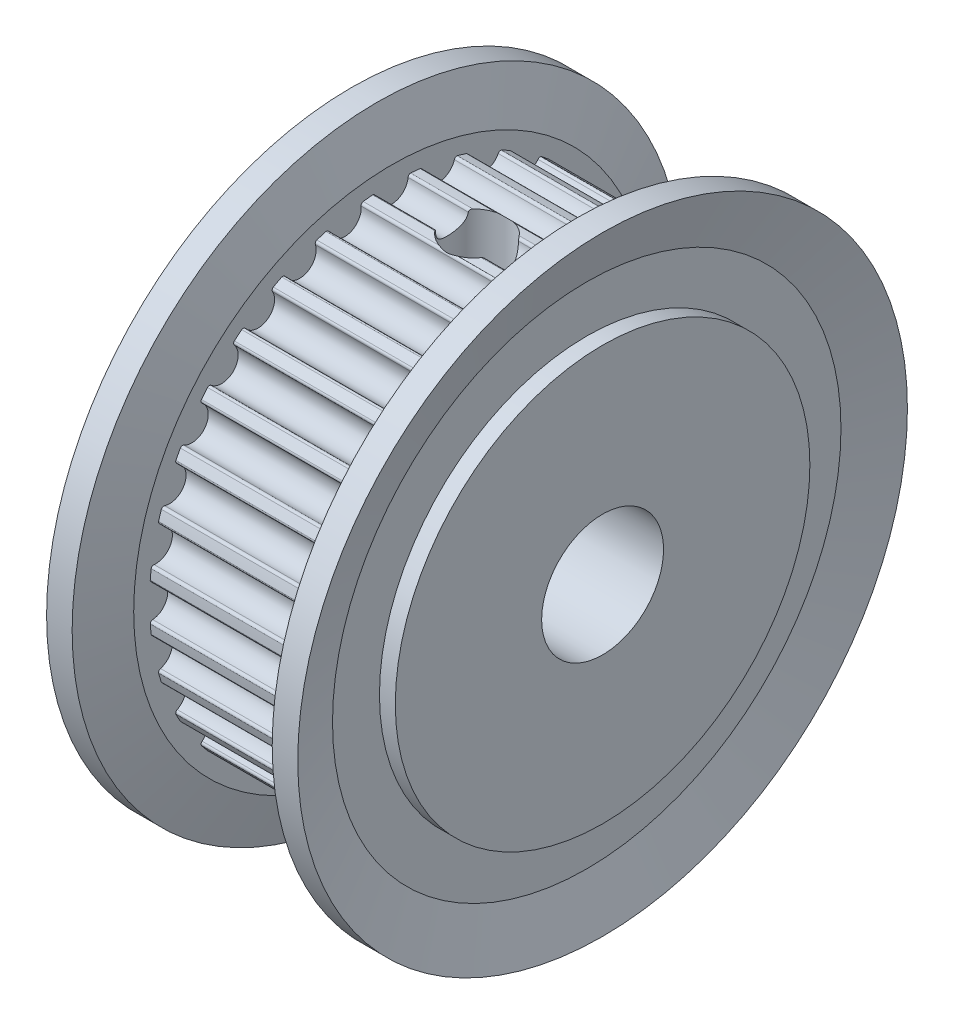
SolidWorks part; units mm, degrees
ref_plane "Front Plane" through (0, 0, 0) normal (0, 0, 1) x (1, 0, 0)
ref_plane "Top Plane" through (0, 0, 0) normal (0, 1, 0) x (1, 0, 0)
ref_plane "Right Plane" through (0, 0, 0) normal (1, 0, 0) x (0, 0, -1)
ref_plane "Plane1" through (0, 0, 0) normal (0, 0, 1) x (1, 0, 0)
sketch "Sketch1" plane through (0, 0, 0) normal (0, 0, 1) x (1, 0, 0)
  line L0 (-5.15, 0) -> (-5.15, 8.5)
  line L1 (-5.15, 8.5) -> (-3.5, 8.5)
  line L2 (-3.5, 8.5) -> (-3.5, 9.93)
  line L3 (-3.5, 9.93) -> (3.5, 9.93)
  line L4 (3.5, 9.93) -> (3.5, 8.5)
  line L5 (3.5, 8.5) -> (5.15, 8.5)
  line L6 (5.15, 8.5) -> (5.15, 0)
  line L7 (5.15, 0) -> (-5.15, 0)
  line L8 (5.15, 0) -> (-5.15, 0) construction
revolve "Revolve1" add sketch "Sketch1" angle 360 about L8
ref_plane "Plane2" through (0, 0, 0) normal (1, 0, 0) x (0, 0, -1)
sketch "Sketch2" plane through (0, 0, 0) normal (1, 0, 0) x (0, 0, -1)
  line L0 (-0.9509, 10.1405) -> (-0.9273, 9.8885)
  line L1 (-0.9273, 9.8885) -> (-0.793, 9.8993)
  line L2 (0.793, 9.8993) -> (0.9273, 9.8885)
  line L3 (0.9273, 9.8885) -> (0.9509, 10.1405)
  arc A0 (-0.793, 9.8993) -> (-0.6724, 9.7974) centre (-0.784, 9.7876) cw
  arc A1 (-0.6724, 9.7974) -> (0.6724, 9.7974) centre (0, 9.856) ccw
  arc A2 (0.6724, 9.7974) -> (0.793, 9.8993) centre (0.784, 9.7876) cw
  arc A3 (0.9509, 10.1405) -> (-0.9509, 10.1405) centre (0, 0) ccw
extrude "Cut-Extrude1" cut sketch "Sketch2" against normal blind 3.5 and the other way blind 3.5
ref_plane "Plane3" through (0, 0, 0) normal (1, 0, 0) x (0, 0, -1)
sketch "Sketch3" plane through (0, 0, 0) normal (1, 0, 0) x (0, 0, -1)
  line L0 (-2.911, 9.7602) -> (-2.8386, 9.5176)
  line L1 (-2.8386, 9.5176) -> (-2.709, 9.5544)
  line L2 (-1.1535, 9.8638) -> (-1.0197, 9.8794)
  line L3 (-1.0197, 9.8794) -> (-1.0457, 10.1312)
  arc A0 (-2.709, 9.5544) -> (-2.5709, 9.4779) centre (-2.6784, 9.4466) cw
  arc A1 (-2.5709, 9.4779) -> (-1.2518, 9.7403) centre (-1.9228, 9.6666) ccw
  arc A2 (-1.2518, 9.7403) -> (-1.1535, 9.8638) centre (-1.1405, 9.7525) cw
  arc A3 (-1.0457, 10.1312) -> (-2.911, 9.7602) centre (0, 0) ccw
extrude "Cut-Extrude2" cut sketch "Sketch3" against normal blind 3.5 and the other way blind 3.5
ref_plane "Plane4" through (0, 0, 0) normal (1, 0, 0) x (0, 0, -1)
sketch "Sketch4" plane through (0, 0, 0) normal (1, 0, 0) x (0, 0, -1)
  line L0 (-4.7591, 9.0047) -> (-4.6409, 8.781)
  line L1 (-4.6409, 8.781) -> (-4.5209, 8.8423)
  line L2 (-3.0557, 9.4492) -> (-2.9275, 9.4907)
  line L3 (-2.9275, 9.4907) -> (-3.0021, 9.7325)
  arc A0 (-4.5209, 8.8423) -> (-4.3706, 8.7943) centre (-4.4699, 8.7426) cw
  arc A1 (-4.3706, 8.7943) -> (-3.128, 9.3089) centre (-3.7717, 9.1058) ccw
  arc A2 (-3.128, 9.3089) -> (-3.0557, 9.4492) centre (-3.0212, 9.3426) cw
  arc A3 (-3.0021, 9.7325) -> (-4.7591, 9.0047) centre (0, 0) ccw
extrude "Cut-Extrude3" cut sketch "Sketch4" against normal blind 3.5 and the other way blind 3.5
ref_plane "Plane5" through (0, 0, 0) normal (1, 0, 0) x (0, 0, -1)
sketch "Sketch5" plane through (0, 0, 0) normal (1, 0, 0) x (0, 0, -1)
  line L0 (-6.4244, 7.9032) -> (-6.2648, 7.7068)
  line L1 (-6.2648, 7.7068) -> (-6.1591, 7.7904)
  line L2 (-4.8404, 8.6715) -> (-4.7228, 8.7372)
  line L3 (-4.7228, 8.7372) -> (-4.8431, 8.9598)
  arc A0 (-6.1591, 7.7904) -> (-6.0023, 7.7726) centre (-6.0896, 7.7026) cw
  arc A1 (-6.0023, 7.7726) -> (-4.884, 8.5198) centre (-5.4757, 8.195) ccw
  arc A2 (-4.884, 8.5198) -> (-4.8404, 8.6715) centre (-4.7858, 8.5737) cw
  arc A3 (-4.8431, 8.9598) -> (-6.4244, 7.9032) centre (0, 0) ccw
extrude "Cut-Extrude4" cut sketch "Sketch5" against normal blind 3.5 and the other way blind 3.5
ref_plane "Plane6" through (0, 0, 0) normal (1, 0, 0) x (0, 0, -1)
sketch "Sketch6" plane through (0, 0, 0) normal (1, 0, 0) x (0, 0, -1)
  line L0 (-7.8428, 6.498) -> (-7.6479, 6.3366)
  line L1 (-7.6479, 6.3366) -> (-7.5606, 6.4391)
  line L2 (-6.4391, 7.5606) -> (-6.3366, 7.6479)
  line L3 (-6.3366, 7.6479) -> (-6.498, 7.8428)
  arc A0 (-7.5606, 6.4391) -> (-7.4033, 6.4523) centre (-7.4753, 6.3665) cw
  arc A1 (-7.4033, 6.4523) -> (-6.4523, 7.4033) centre (-6.9692, 6.9692) ccw
  arc A2 (-6.4523, 7.4033) -> (-6.4391, 7.5606) centre (-6.3665, 7.4753) cw
  arc A3 (-6.498, 7.8428) -> (-7.8428, 6.498) centre (0, 0) ccw
extrude "Cut-Extrude5" cut sketch "Sketch6" against normal blind 3.5 and the other way blind 3.5
ref_plane "Plane7" through (0, 0, 0) normal (1, 0, 0) x (0, 0, -1)
sketch "Sketch7" plane through (0, 0, 0) normal (1, 0, 0) x (0, 0, -1)
  line L0 (-8.9598, 4.8431) -> (-8.7372, 4.7228)
  line L1 (-8.7372, 4.7228) -> (-8.6715, 4.8404)
  line L2 (-7.7904, 6.1591) -> (-7.7068, 6.2648)
  line L3 (-7.7068, 6.2648) -> (-7.9032, 6.4244)
  arc A0 (-8.6715, 4.8404) -> (-8.5198, 4.884) centre (-8.5737, 4.7858) cw
  arc A1 (-8.5198, 4.884) -> (-7.7726, 6.0023) centre (-8.195, 5.4757) ccw
  arc A2 (-7.7726, 6.0023) -> (-7.7904, 6.1591) centre (-7.7026, 6.0896) cw
  arc A3 (-7.9032, 6.4244) -> (-8.9598, 4.8431) centre (0, 0) ccw
extrude "Cut-Extrude6" cut sketch "Sketch7" against normal blind 3.5 and the other way blind 3.5
ref_plane "Plane8" through (0, 0, 0) normal (1, 0, 0) x (0, 0, -1)
sketch "Sketch8" plane through (0, 0, 0) normal (1, 0, 0) x (0, 0, -1)
  line L0 (-9.7325, 3.0021) -> (-9.4907, 2.9275)
  line L1 (-9.4907, 2.9275) -> (-9.4492, 3.0557)
  line L2 (-8.8423, 4.5209) -> (-8.781, 4.6409)
  line L3 (-8.781, 4.6409) -> (-9.0047, 4.7591)
  arc A0 (-9.4492, 3.0557) -> (-9.3089, 3.128) centre (-9.3426, 3.0212) cw
  arc A1 (-9.3089, 3.128) -> (-8.7943, 4.3706) centre (-9.1058, 3.7717) ccw
  arc A2 (-8.7943, 4.3706) -> (-8.8423, 4.5209) centre (-8.7426, 4.4699) cw
  arc A3 (-9.0047, 4.7591) -> (-9.7325, 3.0021) centre (0, 0) ccw
extrude "Cut-Extrude7" cut sketch "Sketch8" against normal blind 3.5 and the other way blind 3.5
ref_plane "Plane9" through (0, 0, 0) normal (1, 0, 0) x (0, 0, -1)
sketch "Sketch9" plane through (0, 0, 0) normal (1, 0, 0) x (0, 0, -1)
  line L0 (-10.1312, 1.0457) -> (-9.8794, 1.0197)
  line L1 (-9.8794, 1.0197) -> (-9.8638, 1.1535)
  line L2 (-9.5544, 2.709) -> (-9.5176, 2.8386)
  line L3 (-9.5176, 2.8386) -> (-9.7602, 2.911)
  arc A0 (-9.8638, 1.1535) -> (-9.7403, 1.2518) centre (-9.7525, 1.1405) cw
  arc A1 (-9.7403, 1.2518) -> (-9.4779, 2.5709) centre (-9.6666, 1.9228) ccw
  arc A2 (-9.4779, 2.5709) -> (-9.5544, 2.709) centre (-9.4466, 2.6784) cw
  arc A3 (-9.7602, 2.911) -> (-10.1312, 1.0457) centre (0, 0) ccw
extrude "Cut-Extrude8" cut sketch "Sketch9" against normal blind 3.5 and the other way blind 3.5
ref_plane "Plane10" through (0, 0, 0) normal (1, 0, 0) x (0, 0, -1)
sketch "Sketch10" plane through (0, 0, 0) normal (1, 0, 0) x (0, 0, -1)
  line L0 (-10.1405, -0.9509) -> (-9.8885, -0.9273)
  line L1 (-9.8885, -0.9273) -> (-9.8993, -0.793)
  line L2 (-9.8993, 0.793) -> (-9.8885, 0.9273)
  line L3 (-9.8885, 0.9273) -> (-10.1405, 0.9509)
  arc A0 (-9.8993, -0.793) -> (-9.7974, -0.6724) centre (-9.7876, -0.784) cw
  arc A1 (-9.7974, -0.6724) -> (-9.7974, 0.6724) centre (-9.856, 0) ccw
  arc A2 (-9.7974, 0.6724) -> (-9.8993, 0.793) centre (-9.7876, 0.784) cw
  arc A3 (-10.1405, 0.9509) -> (-10.1405, -0.9509) centre (0, 0) ccw
extrude "Cut-Extrude9" cut sketch "Sketch10" against normal blind 3.5 and the other way blind 3.5
ref_plane "Plane11" through (0, 0, 0) normal (1, 0, 0) x (0, 0, -1)
sketch "Sketch11" plane through (0, 0, 0) normal (1, 0, 0) x (0, 0, -1)
  line L0 (-9.7602, -2.911) -> (-9.5176, -2.8386)
  line L1 (-9.5176, -2.8386) -> (-9.5544, -2.709)
  line L2 (-9.8638, -1.1535) -> (-9.8794, -1.0197)
  line L3 (-9.8794, -1.0197) -> (-10.1312, -1.0457)
  arc A0 (-9.5544, -2.709) -> (-9.4779, -2.5709) centre (-9.4466, -2.6784) cw
  arc A1 (-9.4779, -2.5709) -> (-9.7403, -1.2518) centre (-9.6666, -1.9228) ccw
  arc A2 (-9.7403, -1.2518) -> (-9.8638, -1.1535) centre (-9.7525, -1.1405) cw
  arc A3 (-10.1312, -1.0457) -> (-9.7602, -2.911) centre (0, 0) ccw
extrude "Cut-Extrude10" cut sketch "Sketch11" against normal blind 3.5 and the other way blind 3.5
ref_plane "Plane12" through (0, 0, 0) normal (1, 0, 0) x (0, 0, -1)
sketch "Sketch12" plane through (0, 0, 0) normal (1, 0, 0) x (0, 0, -1)
  line L0 (-9.0047, -4.7591) -> (-8.781, -4.6409)
  line L1 (-8.781, -4.6409) -> (-8.8423, -4.5209)
  line L2 (-9.4492, -3.0557) -> (-9.4907, -2.9275)
  line L3 (-9.4907, -2.9275) -> (-9.7325, -3.0021)
  arc A0 (-8.8423, -4.5209) -> (-8.7943, -4.3706) centre (-8.7426, -4.4699) cw
  arc A1 (-8.7943, -4.3706) -> (-9.3089, -3.128) centre (-9.1058, -3.7717) ccw
  arc A2 (-9.3089, -3.128) -> (-9.4492, -3.0557) centre (-9.3426, -3.0212) cw
  arc A3 (-9.7325, -3.0021) -> (-9.0047, -4.7591) centre (0, 0) ccw
extrude "Cut-Extrude11" cut sketch "Sketch12" against normal blind 3.5 and the other way blind 3.5
ref_plane "Plane13" through (0, 0, 0) normal (1, 0, 0) x (0, 0, -1)
sketch "Sketch13" plane through (0, 0, 0) normal (1, 0, 0) x (0, 0, -1)
  line L0 (-7.9032, -6.4244) -> (-7.7068, -6.2648)
  line L1 (-7.7068, -6.2648) -> (-7.7904, -6.1591)
  line L2 (-8.6715, -4.8404) -> (-8.7372, -4.7228)
  line L3 (-8.7372, -4.7228) -> (-8.9598, -4.8431)
  arc A0 (-7.7904, -6.1591) -> (-7.7726, -6.0023) centre (-7.7026, -6.0896) cw
  arc A1 (-7.7726, -6.0023) -> (-8.5198, -4.884) centre (-8.195, -5.4757) ccw
  arc A2 (-8.5198, -4.884) -> (-8.6715, -4.8404) centre (-8.5737, -4.7858) cw
  arc A3 (-8.9598, -4.8431) -> (-7.9032, -6.4244) centre (0, 0) ccw
extrude "Cut-Extrude12" cut sketch "Sketch13" against normal blind 3.5 and the other way blind 3.5
ref_plane "Plane14" through (0, 0, 0) normal (1, 0, 0) x (0, 0, -1)
sketch "Sketch14" plane through (0, 0, 0) normal (1, 0, 0) x (0, 0, -1)
  line L0 (-6.498, -7.8428) -> (-6.3366, -7.6479)
  line L1 (-6.3366, -7.6479) -> (-6.4391, -7.5606)
  line L2 (-7.5606, -6.4391) -> (-7.6479, -6.3366)
  line L3 (-7.6479, -6.3366) -> (-7.8428, -6.498)
  arc A0 (-6.4391, -7.5606) -> (-6.4523, -7.4033) centre (-6.3665, -7.4753) cw
  arc A1 (-6.4523, -7.4033) -> (-7.4033, -6.4523) centre (-6.9692, -6.9692) ccw
  arc A2 (-7.4033, -6.4523) -> (-7.5606, -6.4391) centre (-7.4753, -6.3665) cw
  arc A3 (-7.8428, -6.498) -> (-6.498, -7.8428) centre (0, 0) ccw
extrude "Cut-Extrude13" cut sketch "Sketch14" against normal blind 3.5 and the other way blind 3.5
ref_plane "Plane15" through (0, 0, 0) normal (1, 0, 0) x (0, 0, -1)
sketch "Sketch15" plane through (0, 0, 0) normal (1, 0, 0) x (0, 0, -1)
  line L0 (-4.8431, -8.9598) -> (-4.7228, -8.7372)
  line L1 (-4.7228, -8.7372) -> (-4.8404, -8.6715)
  line L2 (-6.1591, -7.7904) -> (-6.2648, -7.7068)
  line L3 (-6.2648, -7.7068) -> (-6.4244, -7.9032)
  arc A0 (-4.8404, -8.6715) -> (-4.884, -8.5198) centre (-4.7858, -8.5737) cw
  arc A1 (-4.884, -8.5198) -> (-6.0023, -7.7726) centre (-5.4757, -8.195) ccw
  arc A2 (-6.0023, -7.7726) -> (-6.1591, -7.7904) centre (-6.0896, -7.7026) cw
  arc A3 (-6.4244, -7.9032) -> (-4.8431, -8.9598) centre (0, 0) ccw
extrude "Cut-Extrude14" cut sketch "Sketch15" against normal blind 3.5 and the other way blind 3.5
ref_plane "Plane16" through (0, 0, 0) normal (1, 0, 0) x (0, 0, -1)
sketch "Sketch16" plane through (0, 0, 0) normal (1, 0, 0) x (0, 0, -1)
  line L0 (-3.0021, -9.7325) -> (-2.9275, -9.4907)
  line L1 (-2.9275, -9.4907) -> (-3.0557, -9.4492)
  line L2 (-4.5209, -8.8423) -> (-4.6409, -8.781)
  line L3 (-4.6409, -8.781) -> (-4.7591, -9.0047)
  arc A0 (-3.0557, -9.4492) -> (-3.128, -9.3089) centre (-3.0212, -9.3426) cw
  arc A1 (-3.128, -9.3089) -> (-4.3706, -8.7943) centre (-3.7717, -9.1058) ccw
  arc A2 (-4.3706, -8.7943) -> (-4.5209, -8.8423) centre (-4.4699, -8.7426) cw
  arc A3 (-4.7591, -9.0047) -> (-3.0021, -9.7325) centre (0, 0) ccw
extrude "Cut-Extrude15" cut sketch "Sketch16" against normal blind 3.5 and the other way blind 3.5
ref_plane "Plane17" through (0, 0, 0) normal (1, 0, 0) x (0, 0, -1)
sketch "Sketch17" plane through (0, 0, 0) normal (1, 0, 0) x (0, 0, -1)
  line L0 (-1.0457, -10.1312) -> (-1.0197, -9.8794)
  line L1 (-1.0197, -9.8794) -> (-1.1535, -9.8638)
  line L2 (-2.709, -9.5544) -> (-2.8386, -9.5176)
  line L3 (-2.8386, -9.5176) -> (-2.911, -9.7602)
  arc A0 (-1.1535, -9.8638) -> (-1.2518, -9.7403) centre (-1.1405, -9.7525) cw
  arc A1 (-1.2518, -9.7403) -> (-2.5709, -9.4779) centre (-1.9228, -9.6666) ccw
  arc A2 (-2.5709, -9.4779) -> (-2.709, -9.5544) centre (-2.6784, -9.4466) cw
  arc A3 (-2.911, -9.7602) -> (-1.0457, -10.1312) centre (0, 0) ccw
extrude "Cut-Extrude16" cut sketch "Sketch17" against normal blind 3.5 and the other way blind 3.5
ref_plane "Plane18" through (0, 0, 0) normal (1, 0, 0) x (0, 0, -1)
sketch "Sketch18" plane through (0, 0, 0) normal (1, 0, 0) x (0, 0, -1)
  line L0 (0.9509, -10.1405) -> (0.9273, -9.8885)
  line L1 (0.9273, -9.8885) -> (0.793, -9.8993)
  line L2 (-0.793, -9.8993) -> (-0.9273, -9.8885)
  line L3 (-0.9273, -9.8885) -> (-0.9509, -10.1405)
  arc A0 (0.793, -9.8993) -> (0.6724, -9.7974) centre (0.784, -9.7876) cw
  arc A1 (0.6724, -9.7974) -> (-0.6724, -9.7974) centre (0, -9.856) ccw
  arc A2 (-0.6724, -9.7974) -> (-0.793, -9.8993) centre (-0.784, -9.7876) cw
  arc A3 (-0.9509, -10.1405) -> (0.9509, -10.1405) centre (0, 0) ccw
extrude "Cut-Extrude17" cut sketch "Sketch18" against normal blind 3.5 and the other way blind 3.5
ref_plane "Plane19" through (0, 0, 0) normal (1, 0, 0) x (0, 0, -1)
sketch "Sketch19" plane through (0, 0, 0) normal (1, 0, 0) x (0, 0, -1)
  line L0 (2.911, -9.7602) -> (2.8386, -9.5176)
  line L1 (2.8386, -9.5176) -> (2.709, -9.5544)
  line L2 (1.1535, -9.8638) -> (1.0197, -9.8794)
  line L3 (1.0197, -9.8794) -> (1.0457, -10.1312)
  arc A0 (2.709, -9.5544) -> (2.5709, -9.4779) centre (2.6784, -9.4466) cw
  arc A1 (2.5709, -9.4779) -> (1.2518, -9.7403) centre (1.9228, -9.6666) ccw
  arc A2 (1.2518, -9.7403) -> (1.1535, -9.8638) centre (1.1405, -9.7525) cw
  arc A3 (1.0457, -10.1312) -> (2.911, -9.7602) centre (0, 0) ccw
extrude "Cut-Extrude18" cut sketch "Sketch19" against normal blind 3.5 and the other way blind 3.5
ref_plane "Plane20" through (0, 0, 0) normal (1, 0, 0) x (0, 0, -1)
sketch "Sketch20" plane through (0, 0, 0) normal (1, 0, 0) x (0, 0, -1)
  line L0 (4.7591, -9.0047) -> (4.6409, -8.781)
  line L1 (4.6409, -8.781) -> (4.5209, -8.8423)
  line L2 (3.0557, -9.4492) -> (2.9275, -9.4907)
  line L3 (2.9275, -9.4907) -> (3.0021, -9.7325)
  arc A0 (4.5209, -8.8423) -> (4.3706, -8.7943) centre (4.4699, -8.7426) cw
  arc A1 (4.3706, -8.7943) -> (3.128, -9.3089) centre (3.7717, -9.1058) ccw
  arc A2 (3.128, -9.3089) -> (3.0557, -9.4492) centre (3.0212, -9.3426) cw
  arc A3 (3.0021, -9.7325) -> (4.7591, -9.0047) centre (0, 0) ccw
extrude "Cut-Extrude19" cut sketch "Sketch20" against normal blind 3.5 and the other way blind 3.5
ref_plane "Plane21" through (0, 0, 0) normal (1, 0, 0) x (0, 0, -1)
sketch "Sketch21" plane through (0, 0, 0) normal (1, 0, 0) x (0, 0, -1)
  line L0 (6.4244, -7.9032) -> (6.2648, -7.7068)
  line L1 (6.2648, -7.7068) -> (6.1591, -7.7904)
  line L2 (4.8404, -8.6715) -> (4.7228, -8.7372)
  line L3 (4.7228, -8.7372) -> (4.8431, -8.9598)
  arc A0 (6.1591, -7.7904) -> (6.0023, -7.7726) centre (6.0896, -7.7026) cw
  arc A1 (6.0023, -7.7726) -> (4.884, -8.5198) centre (5.4757, -8.195) ccw
  arc A2 (4.884, -8.5198) -> (4.8404, -8.6715) centre (4.7858, -8.5737) cw
  arc A3 (4.8431, -8.9598) -> (6.4244, -7.9032) centre (0, 0) ccw
extrude "Cut-Extrude20" cut sketch "Sketch21" against normal blind 3.5 and the other way blind 3.5
ref_plane "Plane22" through (0, 0, 0) normal (1, 0, 0) x (0, 0, -1)
sketch "Sketch22" plane through (0, 0, 0) normal (1, 0, 0) x (0, 0, -1)
  line L0 (7.8428, -6.498) -> (7.6479, -6.3366)
  line L1 (7.6479, -6.3366) -> (7.5606, -6.4391)
  line L2 (6.4391, -7.5606) -> (6.3366, -7.6479)
  line L3 (6.3366, -7.6479) -> (6.498, -7.8428)
  arc A0 (7.5606, -6.4391) -> (7.4033, -6.4523) centre (7.4753, -6.3665) cw
  arc A1 (7.4033, -6.4523) -> (6.4523, -7.4033) centre (6.9692, -6.9692) ccw
  arc A2 (6.4523, -7.4033) -> (6.4391, -7.5606) centre (6.3665, -7.4753) cw
  arc A3 (6.498, -7.8428) -> (7.8428, -6.498) centre (0, 0) ccw
extrude "Cut-Extrude21" cut sketch "Sketch22" against normal blind 3.5 and the other way blind 3.5
ref_plane "Plane23" through (0, 0, 0) normal (1, 0, 0) x (0, 0, -1)
sketch "Sketch23" plane through (0, 0, 0) normal (1, 0, 0) x (0, 0, -1)
  line L0 (8.9598, -4.8431) -> (8.7372, -4.7228)
  line L1 (8.7372, -4.7228) -> (8.6715, -4.8404)
  line L2 (7.7904, -6.1591) -> (7.7068, -6.2648)
  line L3 (7.7068, -6.2648) -> (7.9032, -6.4244)
  arc A0 (8.6715, -4.8404) -> (8.5198, -4.884) centre (8.5737, -4.7858) cw
  arc A1 (8.5198, -4.884) -> (7.7726, -6.0023) centre (8.195, -5.4757) ccw
  arc A2 (7.7726, -6.0023) -> (7.7904, -6.1591) centre (7.7026, -6.0896) cw
  arc A3 (7.9032, -6.4244) -> (8.9598, -4.8431) centre (0, 0) ccw
extrude "Cut-Extrude22" cut sketch "Sketch23" against normal blind 3.5 and the other way blind 3.5
ref_plane "Plane24" through (0, 0, 0) normal (1, 0, 0) x (0, 0, -1)
sketch "Sketch24" plane through (0, 0, 0) normal (1, 0, 0) x (0, 0, -1)
  line L0 (9.7325, -3.0021) -> (9.4907, -2.9275)
  line L1 (9.4907, -2.9275) -> (9.4492, -3.0557)
  line L2 (8.8423, -4.5209) -> (8.781, -4.6409)
  line L3 (8.781, -4.6409) -> (9.0047, -4.7591)
  arc A0 (9.4492, -3.0557) -> (9.3089, -3.128) centre (9.3426, -3.0212) cw
  arc A1 (9.3089, -3.128) -> (8.7943, -4.3706) centre (9.1058, -3.7717) ccw
  arc A2 (8.7943, -4.3706) -> (8.8423, -4.5209) centre (8.7426, -4.4699) cw
  arc A3 (9.0047, -4.7591) -> (9.7325, -3.0021) centre (0, 0) ccw
extrude "Cut-Extrude23" cut sketch "Sketch24" against normal blind 3.5 and the other way blind 3.5
ref_plane "Plane25" through (0, 0, 0) normal (1, 0, 0) x (0, 0, -1)
sketch "Sketch25" plane through (0, 0, 0) normal (1, 0, 0) x (0, 0, -1)
  line L0 (10.1312, -1.0457) -> (9.8794, -1.0197)
  line L1 (9.8794, -1.0197) -> (9.8638, -1.1535)
  line L2 (9.5544, -2.709) -> (9.5176, -2.8386)
  line L3 (9.5176, -2.8386) -> (9.7602, -2.911)
  arc A0 (9.8638, -1.1535) -> (9.7403, -1.2518) centre (9.7525, -1.1405) cw
  arc A1 (9.7403, -1.2518) -> (9.4779, -2.5709) centre (9.6666, -1.9228) ccw
  arc A2 (9.4779, -2.5709) -> (9.5544, -2.709) centre (9.4466, -2.6784) cw
  arc A3 (9.7602, -2.911) -> (10.1312, -1.0457) centre (0, 0) ccw
extrude "Cut-Extrude24" cut sketch "Sketch25" against normal blind 3.5 and the other way blind 3.5
ref_plane "Plane26" through (0, 0, 0) normal (1, 0, 0) x (0, 0, -1)
sketch "Sketch26" plane through (0, 0, 0) normal (1, 0, 0) x (0, 0, -1)
  line L0 (10.1405, 0.9509) -> (9.8885, 0.9273)
  line L1 (9.8885, 0.9273) -> (9.8993, 0.793)
  line L2 (9.8993, -0.793) -> (9.8885, -0.9273)
  line L3 (9.8885, -0.9273) -> (10.1405, -0.9509)
  arc A0 (9.8993, 0.793) -> (9.7974, 0.6724) centre (9.7876, 0.784) cw
  arc A1 (9.7974, 0.6724) -> (9.7974, -0.6724) centre (9.856, 0) ccw
  arc A2 (9.7974, -0.6724) -> (9.8993, -0.793) centre (9.7876, -0.784) cw
  arc A3 (10.1405, -0.9509) -> (10.1405, 0.9509) centre (0, 0) ccw
extrude "Cut-Extrude25" cut sketch "Sketch26" against normal blind 3.5 and the other way blind 3.5
ref_plane "Plane27" through (0, 0, 0) normal (1, 0, 0) x (0, 0, -1)
sketch "Sketch27" plane through (0, 0, 0) normal (1, 0, 0) x (0, 0, -1)
  line L0 (9.7602, 2.911) -> (9.5176, 2.8386)
  line L1 (9.5176, 2.8386) -> (9.5544, 2.709)
  line L2 (9.8638, 1.1535) -> (9.8794, 1.0197)
  line L3 (9.8794, 1.0197) -> (10.1312, 1.0457)
  arc A0 (9.5544, 2.709) -> (9.4779, 2.5709) centre (9.4466, 2.6784) cw
  arc A1 (9.4779, 2.5709) -> (9.7403, 1.2518) centre (9.6666, 1.9228) ccw
  arc A2 (9.7403, 1.2518) -> (9.8638, 1.1535) centre (9.7525, 1.1405) cw
  arc A3 (10.1312, 1.0457) -> (9.7602, 2.911) centre (0, 0) ccw
extrude "Cut-Extrude26" cut sketch "Sketch27" against normal blind 3.5 and the other way blind 3.5
ref_plane "Plane28" through (0, 0, 0) normal (1, 0, 0) x (0, 0, -1)
sketch "Sketch28" plane through (0, 0, 0) normal (1, 0, 0) x (0, 0, -1)
  line L0 (9.0047, 4.7591) -> (8.781, 4.6409)
  line L1 (8.781, 4.6409) -> (8.8423, 4.5209)
  line L2 (9.4492, 3.0557) -> (9.4907, 2.9275)
  line L3 (9.4907, 2.9275) -> (9.7325, 3.0021)
  arc A0 (8.8423, 4.5209) -> (8.7943, 4.3706) centre (8.7426, 4.4699) cw
  arc A1 (8.7943, 4.3706) -> (9.3089, 3.128) centre (9.1058, 3.7717) ccw
  arc A2 (9.3089, 3.128) -> (9.4492, 3.0557) centre (9.3426, 3.0212) cw
  arc A3 (9.7325, 3.0021) -> (9.0047, 4.7591) centre (0, 0) ccw
extrude "Cut-Extrude27" cut sketch "Sketch28" against normal blind 3.5 and the other way blind 3.5
ref_plane "Plane29" through (0, 0, 0) normal (1, 0, 0) x (0, 0, -1)
sketch "Sketch29" plane through (0, 0, 0) normal (1, 0, 0) x (0, 0, -1)
  line L0 (7.9032, 6.4244) -> (7.7068, 6.2648)
  line L1 (7.7068, 6.2648) -> (7.7904, 6.1591)
  line L2 (8.6715, 4.8404) -> (8.7372, 4.7228)
  line L3 (8.7372, 4.7228) -> (8.9598, 4.8431)
  arc A0 (7.7904, 6.1591) -> (7.7726, 6.0023) centre (7.7026, 6.0896) cw
  arc A1 (7.7726, 6.0023) -> (8.5198, 4.884) centre (8.195, 5.4757) ccw
  arc A2 (8.5198, 4.884) -> (8.6715, 4.8404) centre (8.5737, 4.7858) cw
  arc A3 (8.9598, 4.8431) -> (7.9032, 6.4244) centre (0, 0) ccw
extrude "Cut-Extrude28" cut sketch "Sketch29" against normal blind 3.5 and the other way blind 3.5
ref_plane "Plane30" through (0, 0, 0) normal (1, 0, 0) x (0, 0, -1)
sketch "Sketch30" plane through (0, 0, 0) normal (1, 0, 0) x (0, 0, -1)
  line L0 (6.498, 7.8428) -> (6.3366, 7.6479)
  line L1 (6.3366, 7.6479) -> (6.4391, 7.5606)
  line L2 (7.5606, 6.4391) -> (7.6479, 6.3366)
  line L3 (7.6479, 6.3366) -> (7.8428, 6.498)
  arc A0 (6.4391, 7.5606) -> (6.4523, 7.4033) centre (6.3665, 7.4753) cw
  arc A1 (6.4523, 7.4033) -> (7.4033, 6.4523) centre (6.9692, 6.9692) ccw
  arc A2 (7.4033, 6.4523) -> (7.5606, 6.4391) centre (7.4753, 6.3665) cw
  arc A3 (7.8428, 6.498) -> (6.498, 7.8428) centre (0, 0) ccw
extrude "Cut-Extrude29" cut sketch "Sketch30" against normal blind 3.5 and the other way blind 3.5
ref_plane "Plane31" through (0, 0, 0) normal (1, 0, 0) x (0, 0, -1)
sketch "Sketch31" plane through (0, 0, 0) normal (1, 0, 0) x (0, 0, -1)
  line L0 (4.8431, 8.9598) -> (4.7228, 8.7372)
  line L1 (4.7228, 8.7372) -> (4.8404, 8.6715)
  line L2 (6.1591, 7.7904) -> (6.2648, 7.7068)
  line L3 (6.2648, 7.7068) -> (6.4244, 7.9032)
  arc A0 (4.8404, 8.6715) -> (4.884, 8.5198) centre (4.7858, 8.5737) cw
  arc A1 (4.884, 8.5198) -> (6.0023, 7.7726) centre (5.4757, 8.195) ccw
  arc A2 (6.0023, 7.7726) -> (6.1591, 7.7904) centre (6.0896, 7.7026) cw
  arc A3 (6.4244, 7.9032) -> (4.8431, 8.9598) centre (0, 0) ccw
extrude "Cut-Extrude30" cut sketch "Sketch31" against normal blind 3.5 and the other way blind 3.5
ref_plane "Plane32" through (0, 0, 0) normal (1, 0, 0) x (0, 0, -1)
sketch "Sketch32" plane through (0, 0, 0) normal (1, 0, 0) x (0, 0, -1)
  line L0 (3.0021, 9.7325) -> (2.9275, 9.4907)
  line L1 (2.9275, 9.4907) -> (3.0557, 9.4492)
  line L2 (4.5209, 8.8423) -> (4.6409, 8.781)
  line L3 (4.6409, 8.781) -> (4.7591, 9.0047)
  arc A0 (3.0557, 9.4492) -> (3.128, 9.3089) centre (3.0212, 9.3426) cw
  arc A1 (3.128, 9.3089) -> (4.3706, 8.7943) centre (3.7717, 9.1058) ccw
  arc A2 (4.3706, 8.7943) -> (4.5209, 8.8423) centre (4.4699, 8.7426) cw
  arc A3 (4.7591, 9.0047) -> (3.0021, 9.7325) centre (0, 0) ccw
extrude "Cut-Extrude31" cut sketch "Sketch32" against normal blind 3.5 and the other way blind 3.5
ref_plane "Plane33" through (0, 0, 0) normal (1, 0, 0) x (0, 0, -1)
sketch "Sketch33" plane through (0, 0, 0) normal (1, 0, 0) x (0, 0, -1)
  line L0 (1.0457, 10.1312) -> (1.0197, 9.8794)
  line L1 (1.0197, 9.8794) -> (1.1535, 9.8638)
  line L2 (2.709, 9.5544) -> (2.8386, 9.5176)
  line L3 (2.8386, 9.5176) -> (2.911, 9.7602)
  arc A0 (1.1535, 9.8638) -> (1.2518, 9.7403) centre (1.1405, 9.7525) cw
  arc A1 (1.2518, 9.7403) -> (2.5709, 9.4779) centre (1.9228, 9.6666) ccw
  arc A2 (2.5709, 9.4779) -> (2.709, 9.5544) centre (2.6784, 9.4466) cw
  arc A3 (2.911, 9.7602) -> (1.0457, 10.1312) centre (0, 0) ccw
extrude "Cut-Extrude32" cut sketch "Sketch33" against normal blind 3.5 and the other way blind 3.5
ref_plane "Plane34" through (0, 0, 0) normal (0, 0, 1) x (1, 0, 0)
sketch "Sketch34" plane through (0, 0, 0) normal (0, 0, 1) x (1, 0, 0)
  line L0 (3.5, 8.5) -> (4.5, 8.5)
  line L1 (4.5, 8.5) -> (4.5, 10.425)
  line L2 (4.5, 10.425) -> (5.15, 12.5)
  line L3 (5.15, 12.5) -> (4.1021, 12.5)
  line L4 (4.1021, 12.5) -> (3.5, 10.578)
  line L5 (3.5, 10.578) -> (3.5, 8.5)
  line L6 (50, 0) -> (-50, 0) construction
revolve "Revolve2" add sketch "Sketch34" angle 360 about L6
ref_plane "Plane35" through (0, 0, 0) normal (0, 0, 1) x (1, 0, 0)
sketch "Sketch35" plane through (0, 0, 0) normal (0, 0, 1) x (1, 0, 0)
  line L0 (-5.15, 12.5) -> (-4.5, 10.425)
  line L1 (-4.5, 10.425) -> (-4.5, 8.5)
  line L2 (-4.5, 8.5) -> (-3.5, 8.5)
  line L3 (-3.5, 8.5) -> (-3.5, 10.578)
  line L4 (-3.5, 10.578) -> (-4.1021, 12.5)
  line L5 (-4.1021, 12.5) -> (-5.15, 12.5)
  line L6 (50, 0) -> (-50, 0) construction
revolve "Revolve3" add sketch "Sketch35" angle 360 about L6
ref_plane "Plane36" through (0, 0, 0) normal (0, 0, 1) x (1, 0, 0)
sketch "Sketch36" plane through (0, 0, 0) normal (0, 0, 1) x (1, 0, 0)
  line L0 (-5.15, 0) -> (-5.15, 2.5)
  line L1 (-5.15, 2.5) -> (5.15, 2.5)
  line L2 (5.15, 2.5) -> (5.15, 0)
  line L3 (5.15, 0) -> (-5.15, 0)
  line L4 (5.15, 0) -> (-5.15, 0) construction
revolve "Cut-Revolve1" cut sketch "Sketch36" angle 360 about L4
ref_plane "Plane37" through (0, 0, 0) normal (1, 0, 0) x (0, 0, -1)
sketch "Sketch37" plane through (0, 0, 0) normal (1, 0, 0) x (0, 0, -1)
  line L0 (0, 9.93) -> (1.2295, 9.93)
  line L1 (1.2295, 9.93) -> (1.2295, 0)
  line L2 (1.2295, 0) -> (0, 0)
  line L3 (0, 0) -> (0, 9.93)
  line L4 (0, 0) -> (0, 9.93) construction
revolve "Cut-Revolve2" cut sketch "Sketch37" angle 360 about L4
ref_plane "Plane38" through (0, 0, 0) normal (1, 0, 0) x (0, 0, -1)
sketch "Sketch38" plane through (0, 0, 0) normal (1, 0, 0) x (0, 0, -1)
  line L0 (8.2565, -5.5168) -> (7.5734, -6.5391)
  line L1 (7.5734, -6.5391) -> (-0.6831, -1.0223)
  line L2 (-0.6831, -1.0223) -> (0, 0)
  line L3 (0, 0) -> (8.2565, -5.5168)
  line L4 (0, 0) -> (8.2565, -5.5168) construction
revolve "Cut-Revolve3" cut sketch "Sketch38" angle 360 about L4
